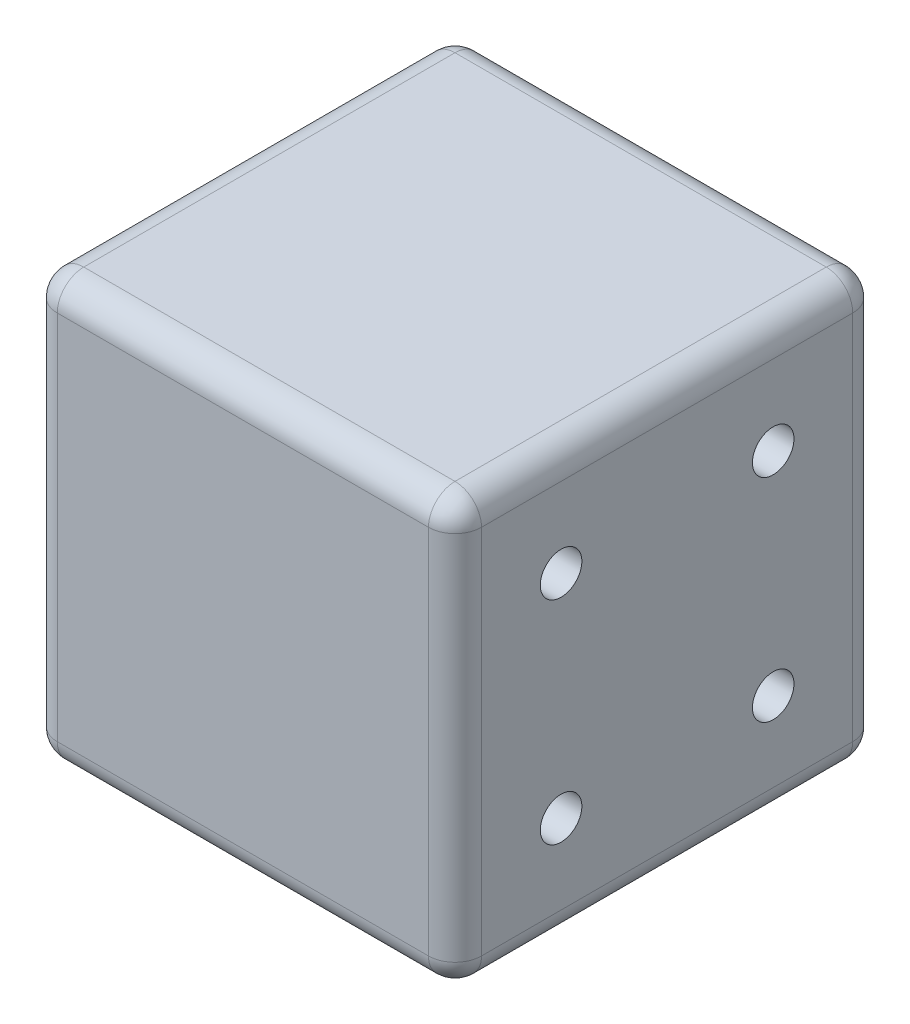
SolidWorks part; units mm, degrees
material "PET"
ref_plane "Front Plane" through (0, 0, 0) normal (0, 0, 1) x (1, 0, 0)
ref_plane "Top Plane" through (0, 0, 0) normal (0, 1, 0) x (1, 0, 0)
ref_plane "Right Plane" through (0, 0, 0) normal (1, 0, 0) x (0, 0, -1)
sketch "Sketch1" plane through (0, 0, 0) normal (0, 0, 1) x (1, 0, 0)
  line L1 (0, 0) -> (50.8, 0)
  line L2 (0, 0) -> (0, 50.8)
  line L3 (0, 50.8) -> (50.8, 50.8)
  line L4 (50.8, 0) -> (50.8, 50.8)
  dimension "D1" = 50.8
  dimension "D2" = 50.8
extrude "Boss-Extrude1" add sketch "Sketch1" against normal blind 50.8
fillet "Fillet1" radius 3.175 12 edges at (0, 25.4, 0) (25.4, 0, 0) (50.8, 25.4, 0) (0, 25.4, -50.8) (25.4, 0, -50.8) (50.8, 25.4, -50.8) (25.4, 50.8, -50.8) (0, 0, -25.4) (50.8, 0, -25.4) (50.8, 50.8, -25.4) (0, 50.8, -25.4) (25.4, 50.8, 0)
sketch "Sketch2" plane through (0, 0, 0) normal (-1, 0, 0) x (0, 0, 1)
  line L0 (-3.175, 0) -> (-47.625, 0) construction
  line L1 (-50.8, 3.175) -> (-50.8, 47.625) construction
  circle A0 centre (-38.1, 12.7) radius 2.4892
  circle A1 centre (-12.7, 12.7) radius 2.4892
  circle A2 centre (-12.7, 38.1) radius 2.4892
  circle A3 centre (-38.1, 38.1) radius 2.4892
  dimension "D1" = 4.9784
  dimension "D6" = 25.4
  dimension "D2" = 12.7
  dimension "D3" = 12.7
  dimension "D7" = 25.4
  dimension "D4" = 2
  dimension "D5" = 2
extrude "Cut-Extrude1" cut sketch "Sketch2" against normal through all
